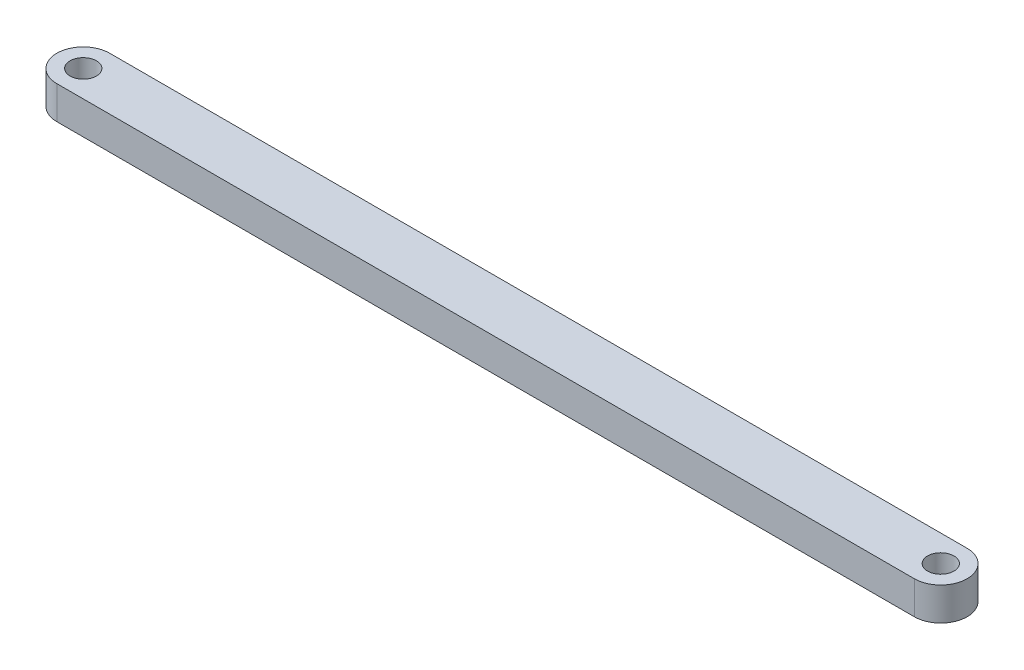
SolidWorks part; units mm, degrees
ref_plane "Front Plane" through (0, 0, 0) normal (0, 0, 1) x (1, 0, 0)
ref_plane "Top Plane" through (0, 0, 0) normal (0, 1, 0) x (1, 0, 0)
ref_plane "Right Plane" through (0, 0, 0) normal (1, 0, 0) x (0, 0, -1)
sketch "Sketch1" plane through (0, 0, 0) normal (0, 1, 0) x (1, 0, 0)
  line L0 (-130, 0) -> (130, 0)
  line L1 (-130, -16) -> (130, -16)
  arc A0 (130, 0) -> (130, -16) centre (130, -8) cw
  arc A1 (-130, 0) -> (-130, -16) centre (-130, -8) ccw
  circle A2 centre (-130, -8) radius 4
  circle A3 centre (130, -8) radius 4
extrude "Boss-Extrude1" add sketch "Sketch1" along normal blind 10
